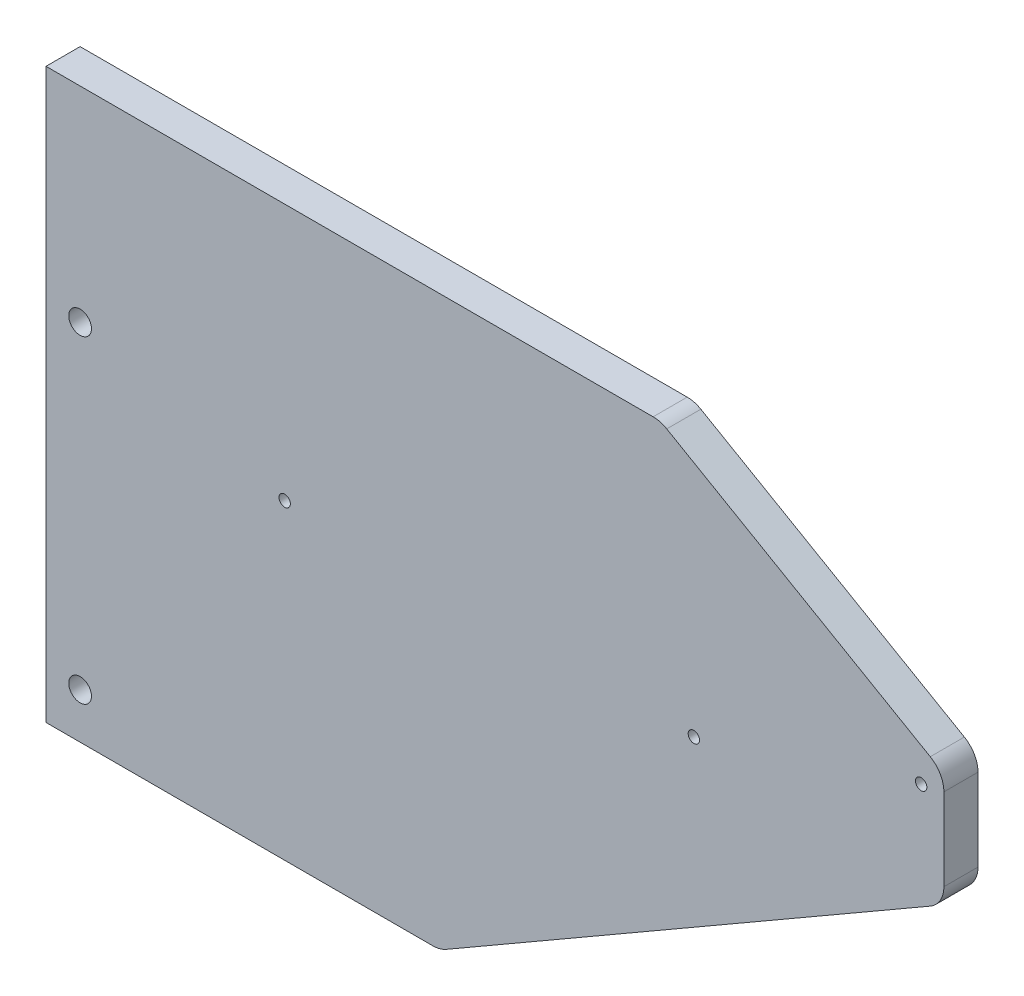
SolidWorks part; units mm, degrees
material "3.3206 (AlMgSi0,5)"
ref_plane "Vorne" through (0, 0, 0) normal (0, 0, 1) x (1, 0, 0)
ref_plane "Oben" through (0, 0, 0) normal (0, 1, 0) x (1, 0, 0)
ref_plane "Rechts" through (0, 0, 0) normal (1, 0, 0) x (0, 0, -1)
sketch "Skizze1" plane through (0, 0, 0) normal (0, 0, 1) x (1, 0, 0)
  line L1 (-204.9179, -153) -> (-375, -153)
  line L2 (-198.9179, -151.3923) -> (14, -28.4641)
  line L3 (-375, -153) -> (-375, 97)
  line L4 (0, 0) -> (-100, 0) construction
  line L5 (-100, 6.5) -> (0, 6.5) construction
  line L6 (10, 16) -> (10, -16) construction
  line L7 (-100, -6.5) -> (0, -6.5) construction
  line L8 (-90, 16) -> (10, 16) construction
  line L10 (-375, 97) -> (-107.923, 97)
  line L11 (-101.923, 95.3923) -> (14, 28.4641)
  line L12 (20, 18.0718) -> (20, 15)
  line L14 (20, -18.0718) -> (20, 15)
  line L15 (-90, -16) -> (10, -16) construction
  line L16 (-90, 16) -> (-90, -16) construction
  arc A0 (20, -18.0718) -> (14, -28.4641) centre (8, -18.0718) cw
  arc A1 (0, -6.5) -> (0, 6.5) centre (0, 0) ccw construction
  arc A2 (14, 28.4641) -> (20, 18.0718) centre (8, 18.0718) cw
  arc A3 (-100, -6.5) -> (-100, 6.5) centre (-100, 0) cw construction
  arc A4 (-107.923, 97) -> (-101.923, 95.3923) centre (-107.923, 85) cw
  circle A5 centre (-270, -16) radius 2.5
  circle A7 centre (-360, 7) radius 5
  circle A8 centre (-360, -133) radius 5
  circle A9 centre (0, 0) radius 25 construction
  circle A10 centre (-90, -16) radius 2.5
  circle A11 centre (10, 16) radius 2.5
  arc A16 (-198.9179, -151.3923) -> (-204.9179, -153) centre (-204.9179, -141) cw
  point P5 (-201.7025, -153)
  point P22 (20, -25)
  point P24 (20, 25)
  point P34 (20, 25)
  dimension "D5" = 153
  dimension "D6" = 250
  dimension "D21" = 50
  dimension "D12" = 20
  dimension "D13" = 50
  dimension "D25" = 12
  dimension "D10" = 140
  dimension "D11" = 15
  dimension "D27" = 10
  dimension "D31" = 5
  dimension "D9" = 375
  dimension "D4" = 20
  dimension "D15" = 280
  dimension "D3" = 173.2975
  dimension "D7" = 13
  dimension "D8" = 30
  dimension "D14" = 30
  dimension "D24" = 100
  dimension "D28" = 10
  dimension "D29" = 32
  dimension "D30" = 100
extrude "Aufsatz-Linear austragen1" add sketch "Skizze1" along normal mid plane 15
hole_wizard "Ø7.0 (7) Durchmesser Bohrung2" [suppressed] positions "Skizze3" profile "Skizze2" hole size "Ø7.0" standard "DIN"
sketch "Skizze3" plane through (20, 0, 0) normal (1, 0, 0) x (0, 0, -1)
  point P0 (0, 0)
sketch "Skizze2" plane through (20, 0, 0) normal (0, 1, 0) x (0, 0, -1)
  line L0 (0, 0) -> (0, 52.103)
  line L1 (0, 52.103) -> (3.5, 50)
  line L2 (3.5, 50) -> (3.5, 0)
  line L5 (3.5, 0) -> (0, 0)
  line L10 (0, 52.103) -> (-3.5, 50) construction
  line L11 (0, -6.35) -> (0, 107.95) construction
  dimension "Bohrerdurchmesser" = 7
  dimension "Bohrungstiefe" = 50
  dimension "Spitzenwinkel" = 118
hole_wizard "Ø7.0 (7) Durchmesser Bohrung1" [suppressed] positions "Skizze5" profile "Skizze4" hole size "Ø7.0" standard "DIN"
sketch "Skizze5" plane through (22.9496, -85.6489, 0) normal (0.2588, -0.9659, 0) x (0.9659, 0.2588, 0)
  line L0 (-208.6334, 0) -> (-228.6334, 0) construction
  line L1 (-208.6334, 7.5) -> (-208.6334, -7.5) construction
  line L2 (-228.6334, -7.5) -> (-228.6334, 0) construction
  line L3 (-248.6334, -7.5) -> (-208.6334, -7.5) construction
  point P0 (-228.6334, 0)
sketch "Skizze4" plane through (-197.8934, -144.8236, 0) normal (0, 0, 1) x (0.9659, 0.2588, 0)
  line L0 (0, 0) -> (0, 52.103)
  line L1 (0, 52.103) -> (3.5, 50)
  line L2 (3.5, 50) -> (3.5, 0)
  line L5 (3.5, 0) -> (0, 0)
  line L10 (0, 52.103) -> (-3.5, 50) construction
  line L11 (0, -6.35) -> (0, 107.95) construction
  dimension "Bohrerdurchmesser" = 7
  dimension "Bohrungstiefe" = 50
  dimension "Spitzenwinkel" = 118
hole_wizard "M8 Gewindebohrung1" [suppressed] positions "Skizze7" profile "Skizze6" tap size "M8" standard "Gabler-Normteile"
sketch "Skizze7" plane through (0, 0, 7.5) normal (0, 0, 1) x (1, 0, 0)
  line L0 (-360, 7) -> (-360, -133) construction
  line L6 (-375, -153) -> (-204.9179, -153) construction
  point P0 (-360, -13)
  point P1 (-360, -113)
  dimension "D1" = 100
  dimension "D2" = 40
sketch "Skizze6" plane through (-360, -13, 7.5) normal (1, 0, 0) x (0, -1, 0)
  line L0 (0, 0) -> (0, 15)
  line L1 (0, 15) -> (3.4, 15)
  line L2 (3.4, 15) -> (3.4, 0)
  line L5 (3.4, 0) -> (0, 0)
  line L11 (0, -6.35) -> (0, 107.95) construction
  dimension "Bohrerdurchmesser" = 6.8
  dimension "Bohrungstiefe" = 15
cosmetic thread "Bohrungsgewinde1" [suppressed] parameters "D2"=8
cosmetic thread "Bohrungsgewinde2" [suppressed] parameters "D2"=8
hole_wizard "M6 Gewindebohrung1" [suppressed] positions "Skizze9" profile "Skizze8" tap size "M6" standard "Gabler-Normteile"
sketch "Skizze9" plane through (0, 0, 7.5) normal (0, 0, 1) x (1, 0, 0)
  line L0 (0, 0) -> (-90, 0) construction
  line L3 (10, 16) -> (-90, 16) construction
  line L5 (-90, -16) -> (10, -16) construction
  line L7 (10, 16) -> (10, -16) construction
  line L9 (-90, -16) -> (-90, 16) construction
  line L32 (-38, 38.5682) -> (-38, -40) construction
  line L33 (-375, 97) -> (-375, -153) construction
  line L34 (-375, -153) -> (-204.9179, -153) construction
  line L35 (-182.6554, -127.5694) -> (-52.7516, -52.5694) construction
  line L37 (-198.9179, -151.3923) -> (14, -28.4641) construction
  line L38 (-90, 16) -> (-270, 16) construction
  line L39 (-270, 16) -> (-270, -16) construction
  arc A1 (-204.9179, -153) -> (-198.9179, -151.3923) centre (-204.9179, -141) ccw construction
  point P16 (-90, 16)
  point P18 (10, -16)
  point P104 (-38, 40)
  point P106 (-38, -40)
  point P110 (-350, -140.5)
  point P112 (-245, -140.5)
  point P125 (-182.6554, -127.5694)
  point P127 (-52.7516, -52.5694)
  point P144 (-270, 16)
  dimension "D3" = 12.5
  dimension "D5" = 40
  dimension "D6" = 38
  dimension "D7" = 25
  dimension "D8" = 12.5
  dimension "D9" = 105
  dimension "D10" = 150
  dimension "D11" = 26
sketch "Skizze8" plane through (-270, 16, 7.5) normal (1, 0, 0) x (0, -1, 0)
  line L0 (0, 0) -> (0, 15)
  line L1 (0, 15) -> (2.5, 15)
  line L2 (2.5, 15) -> (2.5, 0)
  line L5 (2.5, 0) -> (0, 0)
  line L11 (0, -6.35) -> (0, 107.95) construction
  dimension "Bohrerdurchmesser" = 5
  dimension "Bohrungstiefe" = 15
cosmetic thread "Bohrungsgewinde5" [suppressed] parameters "D2"=6
cosmetic thread "Bohrungsgewinde6" [suppressed] parameters "D2"=6
cosmetic thread "Bohrungsgewinde15" [suppressed] parameters "D2"=6
cosmetic thread "Bohrungsgewinde16" [suppressed] parameters "D2"=6
cosmetic thread "Bohrungsgewinde17" [suppressed] parameters "D2"=6
cosmetic thread "Bohrungsgewinde18" [suppressed] parameters "D2"=6
cosmetic thread "Bohrungsgewinde19" [suppressed] parameters "D2"=6
cosmetic thread "Bohrungsgewinde20" [suppressed] parameters "D2"=6
cosmetic thread "Bohrungsgewinde21" [suppressed] parameters "D2"=6
hole_wizard "Ø8.5 (8.5) Durchmesser Bohrung1" [suppressed] positions "Skizze11" profile "Skizze10" hole size "Ø8.5" standard "Gabler-Normteile"
sketch "Skizze11" plane through (0, 0, 7.5) normal (0, 0, 1) x (1, 0, 0)
  line L11 (-375, -153) -> (-204.9179, -153) construction
  line L13 (-375, 97) -> (-375, -153) construction
  point P39 (-265, -103)
  dimension "D2" = 50
  dimension "D4" = 110
sketch "Skizze10" plane through (-265, -103, 7.5) normal (1, 0, 0) x (0, -1, 0)
  line L0 (0, 0) -> (0, 15)
  line L1 (0, 15) -> (4.25, 15)
  line L2 (4.25, 15) -> (4.25, 0)
  line L5 (4.25, 0) -> (0, 0)
  line L11 (0, -6.35) -> (0, 107.95) construction
  dimension "Bohrerdurchmesser" = 8.5
  dimension "Bohrungstiefe" = 15
hole_wizard "Ø5.0 (5) Durchmesser Bohrung1" [suppressed] positions "Skizze13" profile "Skizze12" hole size "Ø5.0" standard "DIN"
sketch "Skizze13" plane through (0, 0, 7.5) normal (0, 0, 1) x (1, 0, 0)
  line L0 (-384.9322, 13) -> (27.0252, 13) construction
  line L3 (-375, 97) -> (-375, -153) construction
  line L5 (-375, -153) -> (-204.9179, -153) construction
  line L6 (-240, 13) -> (-240, 97) construction
  line L7 (-107.923, 97) -> (-375, 97) construction
  point P0 (-340, 13)
  point P9 (-240, 13)
  point P11 (-140, 13)
  dimension "D1" = 166
  dimension "D2" = 200
  dimension "D3" = 135
sketch "Skizze12" plane through (-340, 13, 7.5) normal (1, 0, 0) x (0, -1, 0)
  line L0 (0, 0) -> (0, 21.5022)
  line L1 (0, 21.5022) -> (2.5, 20)
  line L2 (2.5, 20) -> (2.5, 0)
  line L5 (2.5, 0) -> (0, 0)
  line L10 (0, 21.5022) -> (-2.5, 20) construction
  line L11 (0, -6.35) -> (0, 107.95) construction
  dimension "Bohrerdurchmesser" = 5
  dimension "Bohrungstiefe" = 20
  dimension "Spitzenwinkel" = 118
sketch "Skizze14" plane through (0, 0, 7.5) normal (0, 0, 1) x (1, 0, 0)
  line L0 (-375, 97) -> (-375, -153) construction
  line L10 (-335, 43.5) -> (-205, 43.5) construction
  line L11 (-205, 43.5) -> (-75, 43.5) construction
  line L13 (-375, -153) -> (-204.9179, -153) construction
  circle A0 centre (-335, 43.5) radius 3.5
  circle A1 centre (-205, 43.5) radius 3.5
  circle A2 centre (-75, 43.5) radius 3.5
  dimension "D1" = 7
  dimension "D2" = 130
  dimension "D3" = 196.5
  dimension "D4" = 40
extrude "Schnitt-Linear austragen1" [suppressed] cut sketch "Skizze14" against normal through all
sketch "A1 SPANNSKIZE" [suppressed] plane through (0, 0, 7.5) normal (0, 0, 1) x (1, 0, 0)
  line L0 (-107.923, 97) -> (20, 97)
  line L1 (20, 97) -> (20, -153)
  line L2 (20, -153) -> (-204.9179, -153)
  line L3 (20, -18.0718) -> (20, 18.0718) construction
  line L5 (-107.923, 97) -> (-375, 97) construction
  line L6 (-5, 107) -> (25, 107)
  line L7 (-5, 107) -> (-5, 77)
  line L8 (-5, 77) -> (25, 77)
  line L9 (-45, -121) -> (-15, -121)
  line L10 (-45, -121) -> (-45, -151)
  line L11 (-45, -151) -> (-15, -151)
  line L12 (-15, -121) -> (-15, -151)
  line L13 (-373, -48) -> (-343, -48)
  line L14 (-373, -48) -> (-373, -78)
  line L15 (-373, -78) -> (-343, -78)
  line L16 (-343, -48) -> (-343, -78)
  line L17 (-315, 95) -> (-285, 95)
  line L18 (-315, 95) -> (-315, 65)
  line L19 (-315, 65) -> (-285, 65)
  line L20 (-285, 95) -> (-285, 65)
  line L21 (25, 107) -> (25, 77)
  line L22 (-375, 97) -> (-375, -153) construction
  line L23 (-375, -153) -> (-204.9179, -153) construction
  dimension "D1" = 30
  dimension "D2" = 32
  dimension "D3" = 32
  dimension "D4" = 25
  dimension "D5" = 20
  dimension "D6" = 60
  dimension "D7" = 75
  dimension "D8" = 32
  dimension "D9" = 65
chamfer "Fase1" [suppressed] distance 0.5 angle 45
hole_wizard "M5 Gewindebohrung1" [suppressed] positions "Skizze16" profile "Skizze15" tap size "M5" standard "Gabler-Normteile"
sketch "Skizze16" plane through (0, 0, -7.5) normal (0, 0, -1) x (-1, 0, 0)
  line L0 (375, 97) -> (375, -153) construction
  line L1 (107.923, 97) -> (375, 97) construction
  point P0 (225, 83)
  point P2 (225, 68)
  dimension "D1" = 150
  dimension "D2" = 15
  dimension "D3" = 14
sketch "Skizze15" plane through (-225, 83, -7.5) normal (1, 0, 0) x (0, 1, 0)
  line L0 (0, 0) -> (0, 15)
  line L1 (0, 15) -> (2.1, 15)
  line L2 (2.1, 15) -> (2.1, 0)
  line L5 (2.1, 0) -> (0, 0)
  line L11 (0, -6.35) -> (0, 107.95) construction
  dimension "Bohrerdurchmesser" = 4.2
  dimension "Bohrungstiefe" = 15
cosmetic thread "Bohrungsgewinde22" [suppressed] parameters "D2"=5
cosmetic thread "Bohrungsgewinde23" [suppressed] parameters "D2"=5
